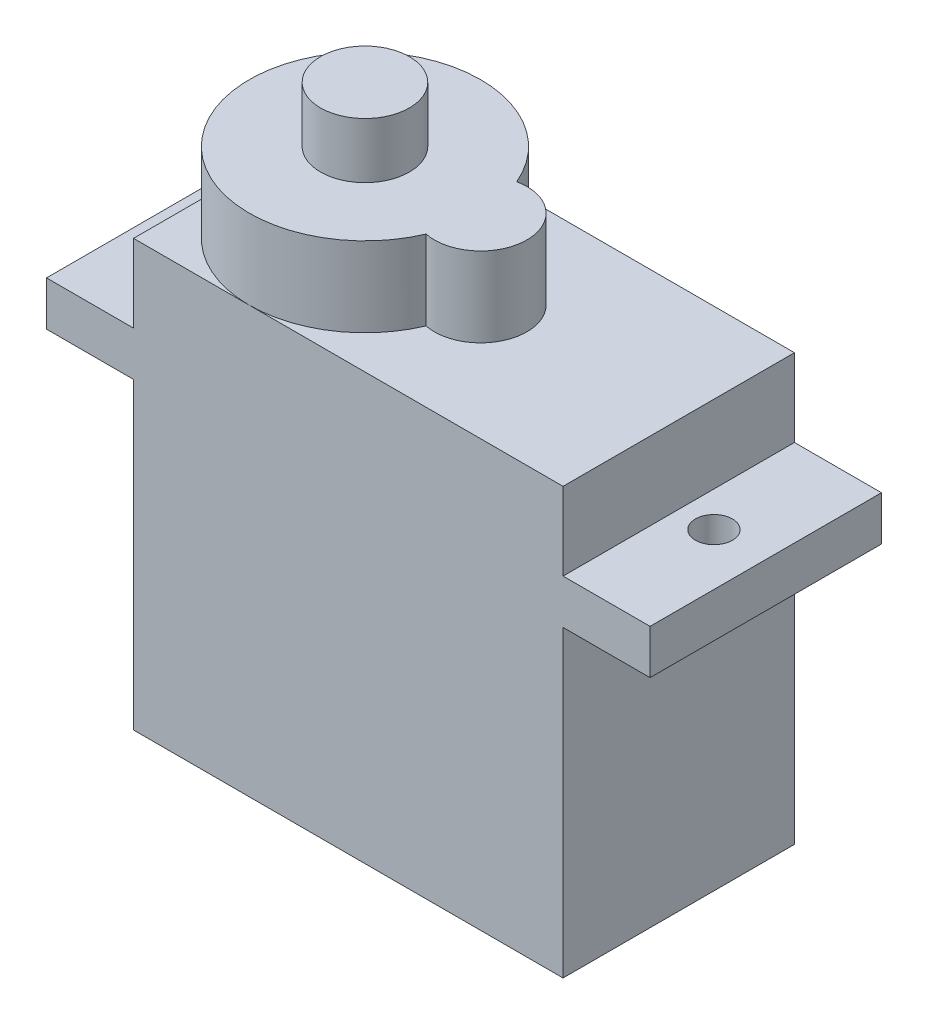
SolidWorks part; units mm, degrees
material "ABS"
ref_plane "Front Plane" through (0, 0, 0) normal (0, 0, 1) x (1, 0, 0)
ref_plane "Top Plane" through (0, 0, 0) normal (0, 1, 0) x (1, 0, 0)
ref_plane "Right Plane" through (0, 0, 0) normal (1, 0, 0) x (0, 0, -1)
sketch "Sketch2" plane through (0, 0, 0) normal (0, 1, 0) x (1, 0, 0)
  line L1 (0, 0) -> (23.2, 0)
  line L2 (0, 0) -> (0, 12.5)
  line L3 (0, 12.5) -> (23.2, 12.5)
  line L4 (23.2, 0) -> (23.2, 12.5)
  dimension "D1" = 23.2
  dimension "D2" = 12.5
extrude "Boss-Extrude1" add sketch "Sketch2" along normal blind 16.4
sketch "Sketch3" plane through (0, 16.4, 0) normal (0, 1, 0) x (1, 0, 0)
  line L0 (0, 0) -> (23.2, 0) construction
  line L1 (-4.7, 0) -> (27.9, 0)
  line L2 (-4.7, 0) -> (-4.7, 12.5)
  line L3 (-4.7, 12.5) -> (27.9, 12.5)
  line L4 (27.9, 0) -> (27.9, 12.5)
  line L5 (23.2, 12.5) -> (0, 12.5) construction
  line L6 (-1.9, 6.25) -> (25.1, 6.25) construction
  circle A0 centre (-1.9, 6.25) radius 1
  circle A1 centre (25.1, 6.25) radius 1
  point P4 (11.6, 0)
  point P7 (11.6, 0)
  point P8 (11.6, 12.5)
  point P11 (11.6, 12.5)
  point P18 (-4.7, 6.25)
  point P20 (11.6, 6.25)
  dimension "D3" = 2
  dimension "D4" = 2
  dimension "D1" = 32.6
  dimension "D2" = 27
extrude "Boss-Extrude2" add sketch "Sketch3" along normal blind 2.4
sketch "Sketch4" plane through (0, 18.8, 0) normal (0, 1, 0) x (1, 0, 0)
  line L0 (27.9, 12.5) -> (-4.7, 12.5) construction
  line L1 (0, 0) -> (23.2, 0)
  line L2 (0, 0) -> (0, 12.5)
  line L3 (0, 12.5) -> (23.2, 12.5)
  line L4 (23.2, 0) -> (23.2, 12.5)
  line L5 (23.2, 0) -> (23.2, 12.5) construction
extrude "Boss-Extrude3" add sketch "Sketch4" along normal blind 4.2
sketch "Sketch5" plane through (0, 23, 0) normal (0, 1, 0) x (1, 0, 0)
  line L0 (0, 0) -> (23.2, 0) construction
  line L1 (0, 12.5) -> (0, 0) construction
  line L2 (23.2, 12.5) -> (0, 12.5) construction
  circle A0 centre (6.25, 6.25) radius 6.25
  circle A1 centre (12.5, 6.25) radius 2.5
  dimension "D1" = 5
extrude "Boss-Extrude4" add sketch "Sketch5" along normal blind 4.3 contours A0 A1 | A0 A1 | A1 A0
sketch "Sketch6" plane through (0, 27.3, 0) normal (0, 1, 0) x (1, 0, 0)
  circle A0 centre (6.25, 6.25) radius 2.4
  arc A1 (12, 8.6995) -> (12, 3.8005) centre (6.25, 6.25) ccw construction
  dimension "D1" = 4.8
extrude "Boss-Extrude5" add sketch "Sketch6" along normal blind 3 contours A0
sketch "Sketch7" plane through (0, 0, 0) normal (-1, 0, 0) x (0, 0, 1)
  line L0 (-12.5, 0) -> (0, 0) construction
  circle A0 centre (-7.266, 5) radius 0.5
  circle A1 centre (-6.25, 5) radius 0.5
  circle A2 centre (-5.234, 5) radius 0.5
  point P10 (-6.25, 0)
  dimension "D2" = 1
  dimension "D1" = 5
  dimension "D4" = 1.016
  dimension "D3" = 3
extrude "Boss-Extrude8" add sketch "Sketch7" along normal blind 2.54 contours A1 | A0 | A2
